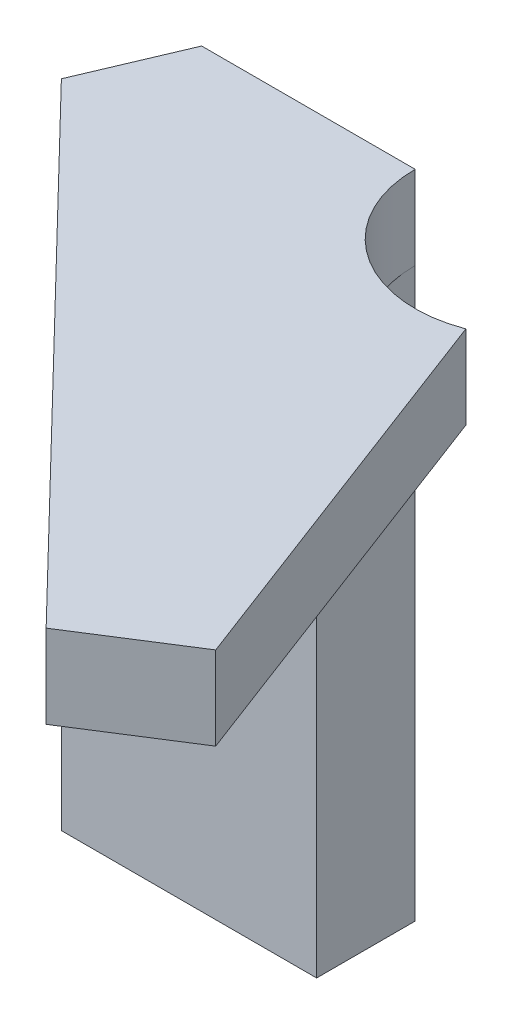
SolidWorks part; units mm, degrees
material "Custom Plastic"
ref_plane "X-Y Datum" through (0, 0, 0) normal (0, 0, 1) x (1, 0, 0)
ref_plane "X-Z Datum" through (0, 0, 0) normal (0, 1, 0) x (1, 0, 0)
ref_plane "Y-Z Datum" through (0, 0, 0) normal (1, 0, 0) x (0, 0, -1)
sketch "Sketch1" plane through (0, 68.54, 0) normal (0, 1, 0) x (1, 0, 0)
  line L0 (-505.1995, -28.9416) -> (-510.9242, -42.4549)
  line L1 (-510.9242, -42.4549) -> (-446.7271, -108.7426)
  line L2 (-446.7271, -108.7426) -> (-432.5063, -99.7069)
  line L3 (-432.5063, -99.7069) -> (-453.4851, -44.4233)
  line L4 (-505.1995, -28.9416) -> (-475.9187, -28.9416)
  arc A0 (-475.9187, -28.9416) -> (-453.4851, -44.4233) centre (-459.36, -28.9417) ccw
  arc A1 (-471.6257, -32.2343) -> (-458.0866, -41.5777) centre (-459.36, -28.9417) ccw construction
extrude "Boss-Extrude1" add sketch "Sketch1" against normal up to surface (11.43 mm away)
sketch "Sketch4" plane through (0, -20.7568, 0) normal (0, 1, 0) x (1, 0, 0)
  line L0 (-505.1995, -28.9416) -> (-510.9242, -42.4549)
  line L1 (-510.9242, -42.4549) -> (-475.9187, -42.4549)
  line L2 (-475.9187, -42.4549) -> (-475.9187, -28.9416)
  line L3 (-475.9187, -28.9416) -> (-505.1995, -28.9416)
extrude "Boss-Extrude2" add sketch "Sketch4" along normal up to surface (77.8668 mm away) up to face at (-471.4707, 57.11, 59.8498)
